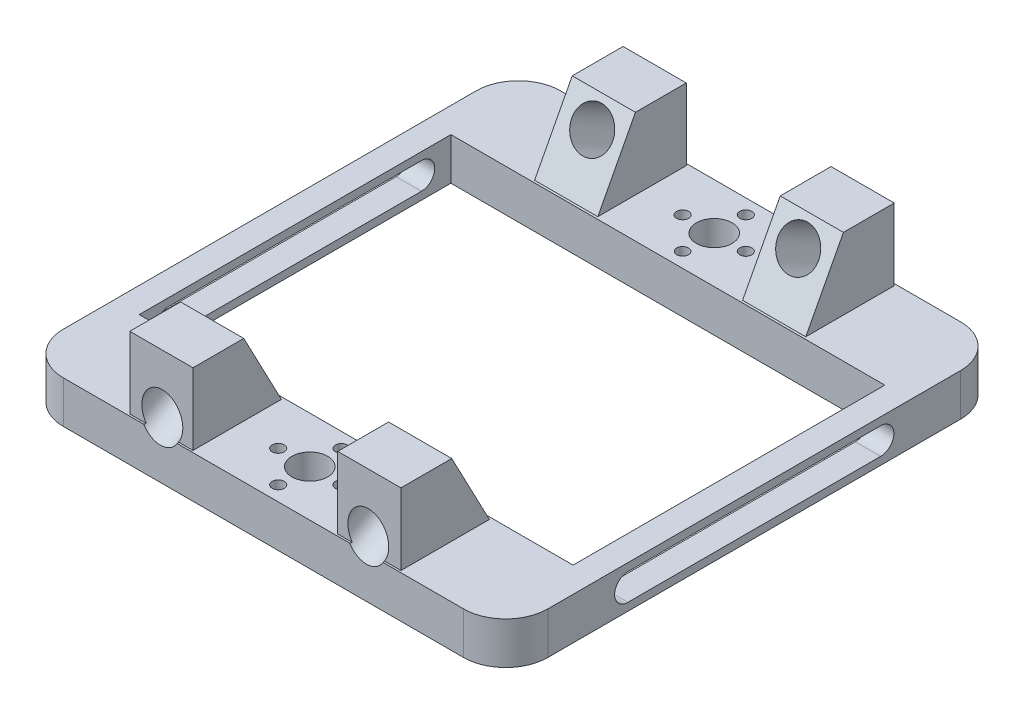
SolidWorks part; units mm, degrees
ref_plane "Front Plane" through (0, 0, 0) normal (0, 0, 1) x (1, 0, 0)
ref_plane "Top Plane" through (0, 0, 0) normal (0, 1, 0) x (1, 0, 0)
ref_plane "Right Plane" through (0, 0, 0) normal (1, 0, 0) x (0, 0, -1)
sketch "Sketch2" plane through (0, 0, 0) normal (0, 1, 0) x (1, 0, 0)
  line L0 (0, 48) -> (0, -48)
  line L1 (-55, 0) -> (55, 0) construction
  line L2 (-57.5, -37) -> (57.5, -37)
  line L3 (-57.5, -37) -> (-57.5, -59)
  line L4 (-57.5, -59) -> (57.5, -59)
  line L5 (57.5, -37) -> (57.5, -59)
  line L6 (-57.5, -37) -> (57.5, -59) construction
  line L7 (-57.5, -59) -> (57.5, -37) construction
  line L8 (-57.5, 59) -> (57.5, 59)
  line L9 (-57.5, 59) -> (-57.5, 37)
  line L10 (-57.5, 37) -> (57.5, 37)
  line L11 (57.5, 59) -> (57.5, 37)
  line L12 (-57.5, 59) -> (57.5, 37) construction
  line L13 (-57.5, 37) -> (57.5, 59) construction
  circle A0 centre (0, 48) radius 4.25
  circle A1 centre (0, -48) radius 4.25
  point P4 (0, 0)
  dimension "D7" = 8.5
  dimension "D1" = 96
  dimension "D2" = 22
  dimension "D3" = 22
  dimension "D4" = 115
  dimension "D5" = 115
  dimension "D6" = 74
extrude "Boss-Extrude1" add sketch "Sketch2" along normal blind 10
sketch "Sketch3" plane through (0, 10, 0) normal (0, 1, 0) x (1, 0, 0)
  line L0 (0, -48) -> (28.3674, -48) construction
  line L1 (28.3674, -48) -> (-30.9998, -17.6631) construction
  line L2 (-5.5, 0) -> (5.5, 0) construction
  line L3 (28.3674, 48) -> (-30.9998, 17.6631) construction
  line L4 (0, 48) -> (28.3674, 48) construction
  circle A0 centre (0, -40.5) radius 1.4
  circle A1 centre (0, -48) radius 4.25 construction
  circle A2 centre (0, -55.5) radius 1.44
  circle A3 centre (7.5, -48) radius 1.44
  circle A4 centre (-7.5, -48) radius 1.44
  circle A5 centre (-7.5, 48) radius 1.44
  circle A6 centre (7.5, 48) radius 1.44
  circle A7 centre (0, 55.5) radius 1.44
  circle A8 centre (0, 40.5) radius 1.4
  dimension "D1" = 7.5
  dimension "D2" = 2.8
  dimension "D6" = 2.88
  dimension "D7" = 2.88
  dimension "D8" = 2.88
  dimension "D3" = 7.5
  dimension "D4" = 7.5
  dimension "D5" = 7.5
sketch "Sketch4" plane through (0, 10, 0) normal (0, 1, 0) x (1, 0, 0)
  line L0 (-57.5, -37) -> (57.5, -37) construction
  line L1 (-51.5, -37) -> (51.5, -37)
  line L2 (-51.5, -37) -> (-51.5, -37.75)
  line L3 (-50.5, -38.75) -> (50.5, -38.75)
  line L4 (51.5, -37) -> (51.5, -37.75)
  line L5 (57.5, -37) -> (57.5, -59) construction
  line L6 (-57.5, -37) -> (-57.5, -59) construction
  arc A0 (50.5, -38.75) -> (51.5, -37.75) centre (50.5, -37.75) ccw
  arc A1 (-51.5, -37.75) -> (-50.5, -38.75) centre (-50.5, -37.75) ccw
  point P14 (-51.5, -38.75)
  dimension "D2" = 1
  dimension "D1" = 1.75
  dimension "6" = 6
  dimension "D3" = 6
extrude "Cut-Extrude3" cut sketch "Sketch3" against normal through all
fillet "Fillet1" radius 10 2 edges at (57.5, 5, -59) (-57.5, 5, -59)
fillet "Fillet2" radius 10 2 edges at (-57.5, 5, 59) (57.5, 5, 59)
sketch "Sketch5" plane through (0, 0, 37) normal (0, 0, -1) x (-1, 0, 0)
  line L0 (57.5, 0) -> (-57.5, 0) construction
  line L1 (-57.5, 10) -> (-51.5, 10)
  line L2 (-57.5, 10) -> (-57.5, 0)
  line L3 (-57.5, 0) -> (-51.5, 0)
  line L4 (-51.5, 10) -> (-51.5, 0)
  dimension "D1" = 6
extrude "Boss-Extrude2" add sketch "Sketch5" along normal up to surface (74 mm away) up to face at (0, 5, -37)
mirror "Mirror3" about plane through (0, 0, 0) normal (1, 0, 0) of "Boss-Extrude2"
sketch "Sketch6" plane through (-51.5, 0, 0) normal (1, 0, 0) x (0, 0, -1)
  line L0 (0, 10) -> (0, 0) construction
  line L1 (49, 10) -> (-49, 10) construction
  line L2 (-30, 5) -> (30, 5) construction
  line L3 (-30, 8.15) -> (30, 8.15)
  line L4 (-30, 1.85) -> (30, 1.85)
  arc A0 (-30, 8.15) -> (-30, 1.85) centre (-30, 5) ccw
  arc A1 (30, 1.85) -> (30, 8.15) centre (30, 5) ccw
  point P7 (0, 5)
  dimension "D2" = 60
  dimension "D1" = 6.3
extrude "Cut-Extrude4" cut sketch "Sketch6" against normal through all both and the other way through all
sketch "Sketch7" plane through (0, 10, 0) normal (0, 1, 0) x (1, 0, 0)
  line L1 (-32.1852, -37.551) -> (-17.1852, -37.551)
  line L2 (-32.1852, -37.551) -> (-32.1852, -58.551)
  line L3 (-32.1852, -58.551) -> (-17.1852, -58.551)
  line L4 (-17.1852, -37.551) -> (-17.1852, -58.551)
  dimension "D1" = 15
  dimension "D2" = 21
extrude "Boss-Extrude3" add sketch "Sketch7" along normal blind 17
sketch "Sketch8" plane through (-17.1852, 0, 0) normal (1, 0, 0) x (0, 0, -1)
  line L0 (-37.551, 10) -> (-46.4841, 27)
  line L1 (-58.551, 27) -> (-37.551, 27) construction
  line L2 (-46.4841, 27) -> (-37.551, 27)
  line L3 (-37.551, 27) -> (-37.551, 10)
  point P5 (-46.4841, 27)
extrude "Cut-Extrude5" cut sketch "Sketch8" against normal through all
sketch "Sketch9" plane through (0, -13.2988, 25.308) normal (0, 0.4652, -0.8852) x (-1, 0, 0)
  line L0 (17.1852, 26.3197) -> (32.1852, 26.3197) construction
  line L1 (32.1852, 26.3197) -> (24.4475, 26.3197) construction
  line L2 (24.4475, 26.3197) -> (24.4475, 40.3084) construction
  circle A0 centre (24.4475, 39.0859) radius 4.85
  point P2 (24.4475, 39.0859)
  dimension "D1" = 9.7
extrude "Cut-Extrude6" cut sketch "Sketch9" against normal through all
mirror "Mirror4" about plane through (0, 0, 0) normal (1, 0, 0) of "Boss-Extrude3", "Cut-Extrude5", "Cut-Extrude6"
mirror "Mirror5" about plane through (0, 0, 0) normal (0, 0, 1) of "Mirror4", "Boss-Extrude3", "Cut-Extrude5", "Cut-Extrude6"
